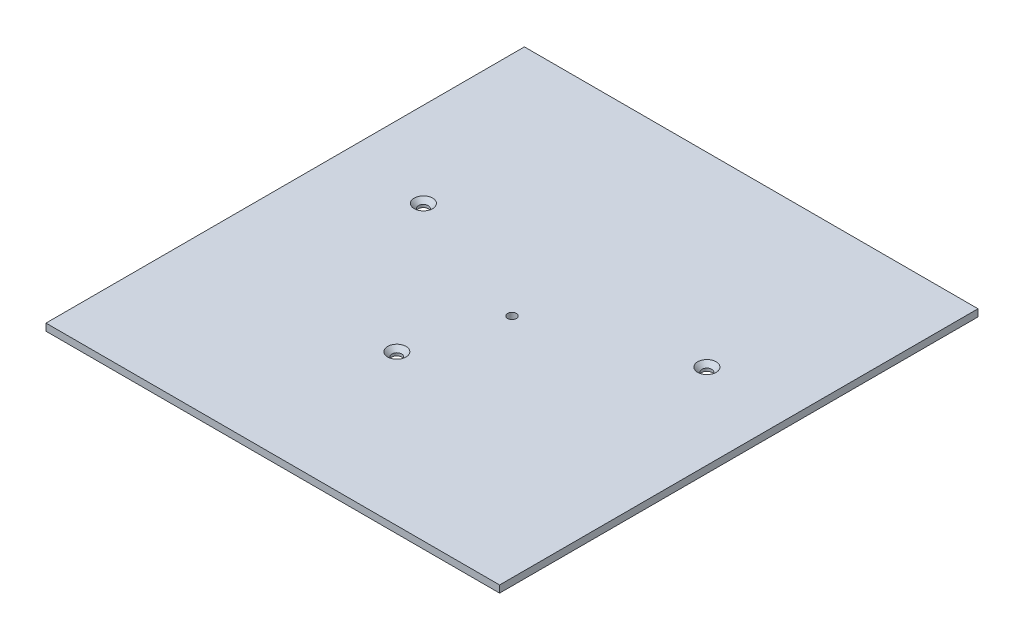
SolidWorks part; units mm, degrees
material "6061 Alloy"
ref_plane "Front Plane" through (0, 0, 0) normal (0, 0, 1) x (1, 0, 0)
ref_plane "Top Plane" through (0, 0, 0) normal (0, 1, 0) x (1, 0, 0)
ref_plane "Right Plane" through (0, 0, 0) normal (1, 0, 0) x (0, 0, -1)
sketch "Sketch1" plane through (0, 0, 0) normal (0, 1, 0) x (1, 0, 0)
  line L0 (0, 0) -> (0, 270)
  line L1 (0, 0) -> (256, 0)
  line L2 (0, 270) -> (256, 270)
  line L3 (256, 0) -> (256, 270)
  dimension "D1" = 270
  dimension "D2" = 256
extrude "Boss-Extrude1" add sketch "Sketch1" along normal blind 4
hole_wizard "CSK for M5 Flat Head Machine Screw1" positions "Sketch3" profile "Sketch2" countersink size "M5" standard "Ansi Metric" end condition through all
sketch "Sketch3" plane through (0, 4, 0) normal (0, 1, 0) x (-1, 0, 0)
  line L0 (0, 0) -> (-256, 0) construction
  line L2 (0, -270) -> (0, 0) construction
  point P0 (-113, -85)
  point P1 (-208, -165)
  point P3 (-48, -165)
  dimension "D1" = 85
  dimension "D2" = 80
  dimension "D3" = 65
  dimension "D4" = 95
  dimension "D5" = 48
sketch "Sketch2" plane through (113, 4, -85) normal (1, 0, 0) x (0, 0, 1)
  line L0 (0, 0) -> (0, 4)
  line L1 (0, 4) -> (2.75, 4)
  line L2 (2.75, 4) -> (2.75, 2.45)
  line L3 (2.75, 2.45) -> (5.2, 0)
  line L5 (5.2, 0) -> (0, 0)
  line L6 (-2.75, 2.45) -> (-5.2, 0) construction
  line L11 (0, -6.35) -> (0, 107.95) construction
  dimension "Thru Hole Dia." = 5.5
  dimension "Thru Hole Depth" = 4
  dimension "Near C'Sink Dia." = 10.4
  dimension "Near C'Sink Angle" = 90
hole_wizard "M6 taped hole - thrmocoupler" positions "Sketch5" profile "Sketch4" tap size "M6x1.0" standard "Ansi Metric" end condition through all
sketch "Sketch5" plane through (0, 4, 0) normal (0, 1, 0) x (-1, 0, 0)
  circle A0 centre (-48, -165) radius 2.75 construction
  point P0 (-128, -135)
  dimension "D1" = 80
  dimension "D2" = 30
sketch "Sketch4" plane through (128, 4, -135) normal (1, 0, 0) x (0, 0, 1)
  line L0 (0, 0) -> (0, 4)
  line L1 (0, 4) -> (2.5, 4)
  line L2 (2.5, 4) -> (2.5, 0)
  line L5 (2.5, 0) -> (0, 0)
  line L11 (0, -6.35) -> (0, 107.95) construction
  dimension "Thru Tap Drill Dia." = 5
  dimension "Thru Tap Drill Depth" = 4
cosmetic thread "Hole Thread1" parameters "D2"=6
